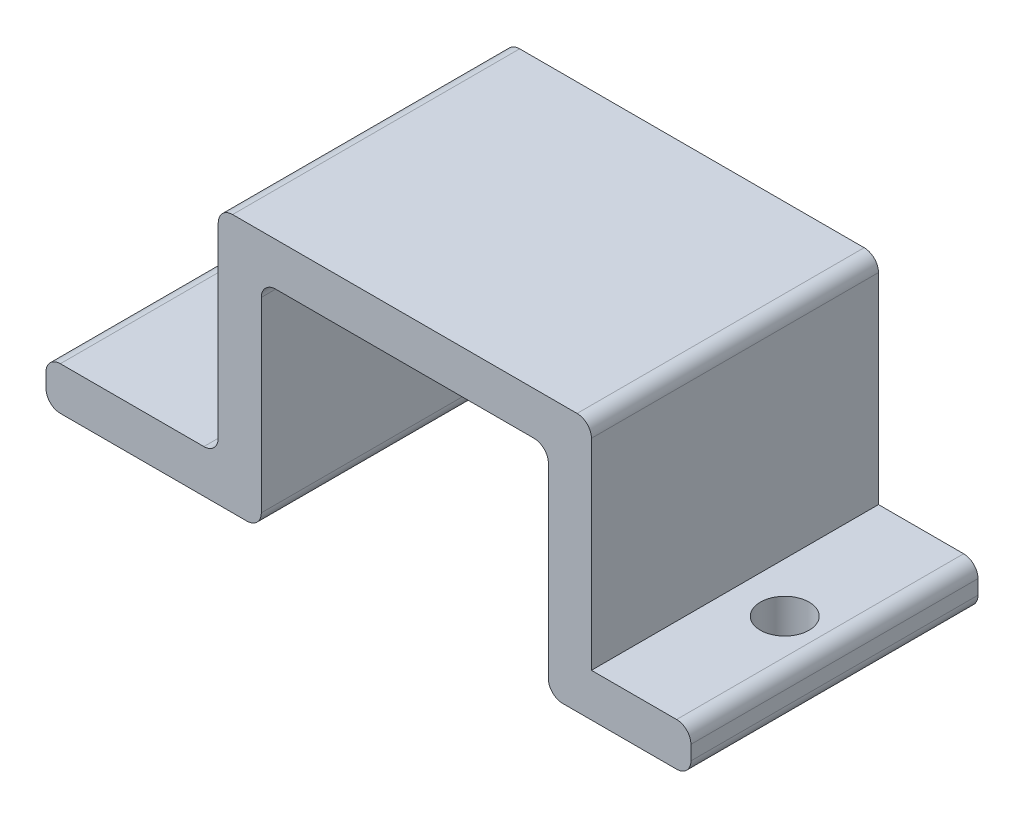
SolidWorks part; units mm, degrees
ref_plane "Front Plane" through (0, 0, 0) normal (0, 0, 1) x (1, 0, 0)
ref_plane "Top Plane" through (0, 0, 0) normal (0, 1, 0) x (1, 0, 0)
ref_plane "Right Plane" through (0, 0, 0) normal (1, 0, 0) x (0, 0, -1)
sketch "Sketch3" plane through (0, 0, 0) normal (0, 0, 1) x (1, 0, 0)
  line L12 (3, 0) -> (3, 15)
  line L13 (3, 15) -> (23, 15)
  line L14 (23, 15) -> (23, 0)
  line L15 (23, 0) -> (26, 0)
  line L16 (26, 0) -> (26, 18)
  line L17 (26, 18) -> (0, 18)
  line L19 (0, 18) -> (0, 0)
  line L20 (0, 0) -> (3, 0)
  dimension "D1" = 3
  dimension "D2" = 3
  dimension "D4" = 20
  dimension "D3" = 15
extrude "Boss-Extrude1" add sketch "Sketch3" along normal blind 20
sketch "Sketch7" plane through (0, 0, 0) normal (0, 1, 0) x (1, 0, 0)
  line L14 (-12, -20) -> (-12, 11) construction
  line L15 (0, -20) -> (-12, -20)
  line L16 (0, -20) -> (0, 0)
  line L17 (0, 0) -> (-12, 0)
  line L18 (-12, -20) -> (-12, 0)
  line L19 (26, 0) -> (32.9317, 0)
  line L20 (26, 0) -> (26, -20)
  line L21 (26, -20) -> (32.9317, -20)
  line L22 (32.9317, 0) -> (32.9317, -20)
  point P5 (29.487, -9.5111)
  point P6 (29.4658, 0)
  point P7 (32.9317, -10)
  point P9 (-6, -10)
  point P15 (29.4658, -10)
  point P33 (-12, -10)
  dimension "D4" = 6
extrude "Boss-Extrude2" add sketch "Sketch7" along normal blind 3
sketch "Sketch8" plane through (0, 3, 0) normal (0, 1, 0) x (1, 0, 0)
  point P2 (29.4658, -10)
  point P5 (-6, -10)
hole_wizard "M3 Clearance Hole2" positions "Sketch8" profile "Sketch9" hole size "M3" standard "ANSI Metric" end condition through all
sketch "Sketch9" plane through (29.4658, 3, 10) normal (1, 0, 0) x (0, 0, 1)
  line L0 (0, 0) -> (0, 3)
  line L1 (0, 3) -> (1.7, 3)
  line L2 (1.7, 3) -> (1.7, 0)
  line L5 (1.7, 0) -> (0, 0)
  line L11 (0, -6.35) -> (0, 107.95) construction
  dimension "Thru Hole Dia." = 3.4
  dimension "Thru Hole Depth" = 3
fillet "Fillet1" radius 1 11 edges at (3, 0, 10) (-12, 0, 10) (-12, 3, 10) (0, 3, 10) (23, 0, 10) (0, 18, 10) (26, 18, 10) (3, 15, 10) (23, 15, 10) (32.9317, 0, 10) (32.9317, 3, 10)
sketch "Sketch4" plane through (0, 0, 0) normal (0, 1, 0) x (1, 0, 0)
  line L0 (-25, -20) -> (-25, 0) construction
  line L1 (-15, 0) -> (-25, 0) construction
  line L2 (0, 0) -> (0, -3.6172) construction
  line L3 (15, 0) -> (-15, 0) construction
  point P0 (-20, -10)
  point P4 (-25, -10)
  point P7 (-20, 0)
  point P8 (20, -10)
hole_wizard "M3 Clearance Hole1" positions "Sketch4" profile "Sketch5" hole size "M3" standard "ANSI Metric"
sketch "Sketch5" plane through (-20, 0, 10) normal (1, 0, 0) x (0, 0, -1)
  line L0 (0, 0) -> (0, 20)
  line L1 (0, 20) -> (1.7, 20)
  line L2 (1.7, 20) -> (1.7, 0)
  line L5 (1.7, 0) -> (0, 0)
  line L11 (0, -6.35) -> (0, 107.95) construction
  dimension "Thru Hole Dia." = 3.4
  dimension "Thru Hole Depth" = 20
